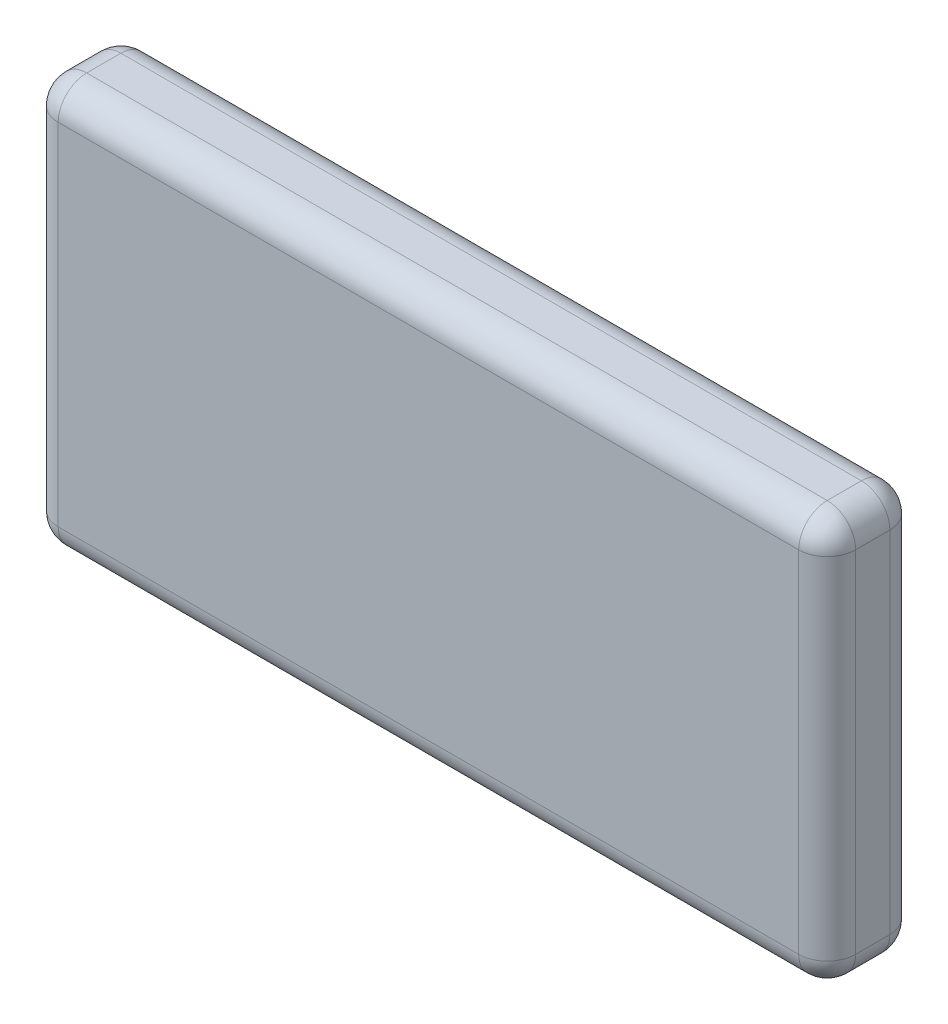
SolidWorks part; units mm, degrees
ref_plane "Front Plane" through (0, 0, 0) normal (0, 0, 1) x (1, 0, 0)
ref_plane "Top Plane" through (0, 0, 0) normal (0, 1, 0) x (1, 0, 0)
ref_plane "Right Plane" through (0, 0, 0) normal (1, 0, 0) x (0, 0, -1)
sketch "Sketch1" plane through (0, 0, 0) normal (0, 0, 1) x (1, 0, 0)
  line L1 (-70, 35.75) -> (70, 35.75)
  line L2 (-70, 35.75) -> (-70, -35.75)
  line L3 (-70, -35.75) -> (70, -35.75)
  line L4 (70, 35.75) -> (70, -35.75)
  line L5 (-70, 35.75) -> (70, -35.75) construction
  line L6 (-70, -35.75) -> (70, 35.75) construction
  point P0 (0, 0)
  dimension "D1" = 140
  dimension "D2" = 71.5
extrude "Boss-Extrude1" add sketch "Sketch1" along normal blind 16
fillet "Fillet1" radius 5 12 edges at (-70, 35.75, 8) (-70, -35.75, 8) (70, -35.75, 8) (70, 35.75, 8) (0, 35.75, 0) (-70, 0, 0) (0, -35.75, 0) (70, 0, 0) (0, -35.75, 16) (-70, 0, 16) (0, 35.75, 16) (70, 0, 16)
